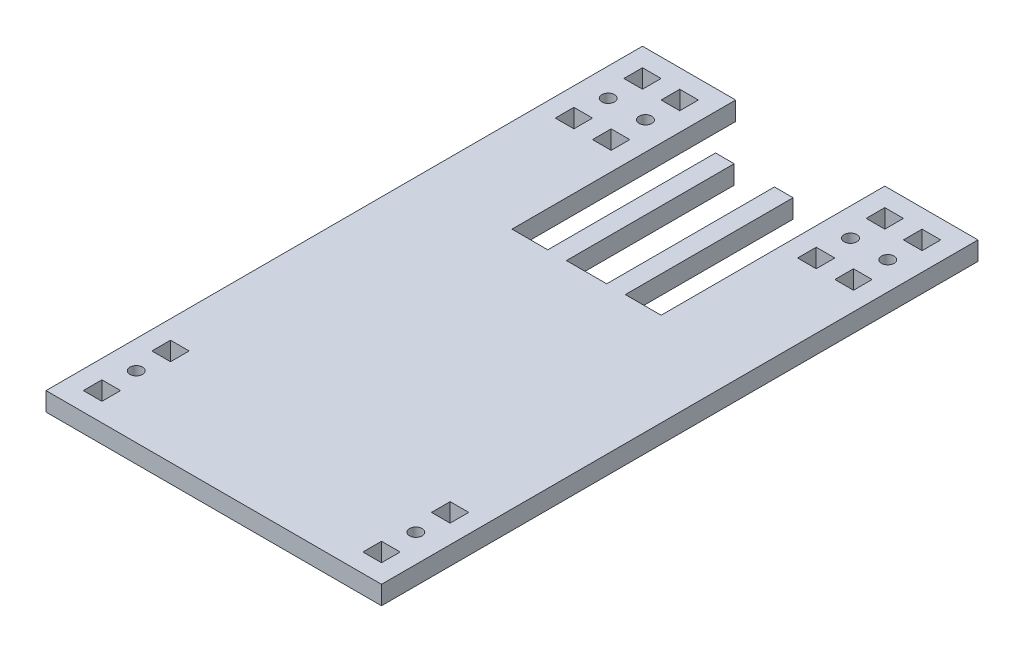
SolidWorks part; units mm, degrees
ref_plane "Front Plane" through (0, 0, 0) normal (0, 0, 1) x (1, 0, 0)
ref_plane "Top Plane" through (0, 0, 0) normal (0, 1, 0) x (1, 0, 0)
ref_plane "Right Plane" through (0, 0, 0) normal (1, 0, 0) x (0, 0, -1)
sketch "Sketch1" plane through (0, 0, 0) normal (0, 1, 0) x (1, 0, 0)
  line L0 (0, 25.4) -> (0, -101.6) construction
  line L1 (-57.15, 101.6) -> (-25.4, 101.6)
  line L2 (-57.15, 101.6) -> (-57.15, -101.6)
  line L3 (-57.15, -101.6) -> (57.15, -101.6)
  line L4 (57.15, 101.6) -> (57.15, -101.6)
  line L5 (-57.15, 101.6) -> (57.15, -101.6) construction
  line L6 (-57.15, -101.6) -> (57.15, 101.6) construction
  line L7 (-57.15, 0) -> (57.15, 0) construction
  line L8 (31.75, 101.6) -> (31.75, -101.6) construction
  line L9 (-31.75, 101.6) -> (-31.75, -101.6) construction
  line L10 (6.858, 82.55) -> (6.858, -101.6) construction
  line L11 (-6.858, 82.55) -> (-6.858, -101.6) construction
  line L12 (-6.858, 82.55) -> (-6.858, 25.4)
  line L13 (-6.858, 25.4) -> (6.858, 25.4)
  line L14 (6.858, 25.4) -> (6.858, 82.55)
  line L15 (6.858, 82.55) -> (13.208, 82.55)
  line L16 (44.45, 101.6) -> (44.45, -101.6) construction
  line L17 (-44.45, 101.6) -> (-44.45, -101.6) construction
  line L18 (13.208, 82.55) -> (13.208, 25.4)
  line L19 (13.208, 25.4) -> (25.4, 25.4)
  line L20 (25.4, 25.4) -> (25.4, 101.6)
  line L21 (25.4, 101.6) -> (57.15, 101.6)
  line L22 (-25.4, 25.4) -> (-25.4, 101.6)
  line L23 (-13.208, 25.4) -> (-25.4, 25.4)
  line L24 (-13.208, 82.55) -> (-13.208, 25.4)
  line L25 (-6.858, 25.4) -> (-6.858, 82.55)
  line L26 (-13.208, 82.55) -> (-6.858, 82.55)
  point P0 (0, 0)
  line B0 (34.925, 65.532) -> (34.925, 95.25) construction
  line B1 (32.766, 80.391) -> (37.084, 80.391) construction
  line B2 (31.75, 88.9) -> (38.1, 88.9)
  line B3 (31.75, 88.9) -> (31.75, 95.25)
  line B4 (31.75, 95.25) -> (38.1, 95.25)
  line B5 (38.1, 88.9) -> (38.1, 95.25)
  line B6 (31.75, 88.9) -> (38.1, 95.25) construction
  line B7 (31.75, 95.25) -> (38.1, 88.9) construction
  line B8 (31.75, 65.532) -> (38.1, 71.882) construction
  line B9 (31.75, 71.882) -> (38.1, 65.532) construction
  line B10 (38.1, 71.882) -> (38.1, 65.532)
  line B11 (31.75, 65.532) -> (38.1, 65.532)
  line B12 (31.75, 71.882) -> (31.75, 65.532)
  line B13 (31.75, 71.882) -> (38.1, 71.882)
  circle B14 centre (34.925, 80.391) radius 2.159
  line B15 (-34.925, 65.532) -> (-34.925, 95.25) construction
  line B16 (-32.766, 80.391) -> (-37.084, 80.391) construction
  line B17 (-31.75, 88.9) -> (-38.1, 88.9)
  line B18 (-31.75, 88.9) -> (-31.75, 95.25)
  line B19 (-31.75, 95.25) -> (-38.1, 95.25)
  line B20 (-38.1, 88.9) -> (-38.1, 95.25)
  line B21 (-31.75, 88.9) -> (-38.1, 95.25) construction
  line B22 (-31.75, 95.25) -> (-38.1, 88.9) construction
  line B23 (-31.75, 65.532) -> (-38.1, 71.882) construction
  line B24 (-31.75, 71.882) -> (-38.1, 65.532) construction
  line B25 (-38.1, 71.882) -> (-38.1, 65.532)
  line B26 (-31.75, 65.532) -> (-38.1, 65.532)
  line B27 (-31.75, 71.882) -> (-31.75, 65.532)
  line B28 (-31.75, 71.882) -> (-38.1, 71.882)
  circle B29 centre (-34.925, 80.391) radius 2.159
  line B30 (47.625, 65.532) -> (47.625, 95.25) construction
  line B31 (45.466, 80.391) -> (49.784, 80.391) construction
  line B32 (44.45, 88.9) -> (50.8, 88.9)
  line B33 (44.45, 88.9) -> (44.45, 95.25)
  line B34 (44.45, 95.25) -> (50.8, 95.25)
  line B35 (50.8, 88.9) -> (50.8, 95.25)
  line B36 (44.45, 88.9) -> (50.8, 95.25) construction
  line B37 (44.45, 95.25) -> (50.8, 88.9) construction
  line B38 (44.45, 65.532) -> (50.8, 71.882) construction
  line B39 (44.45, 71.882) -> (50.8, 65.532) construction
  line B40 (50.8, 71.882) -> (50.8, 65.532)
  line B41 (44.45, 65.532) -> (50.8, 65.532)
  line B42 (44.45, 71.882) -> (44.45, 65.532)
  line B43 (44.45, 71.882) -> (50.8, 71.882)
  circle B44 centre (47.625, 80.391) radius 2.159
  line B45 (-47.625, 65.532) -> (-47.625, 95.25) construction
  line B46 (-45.466, 80.391) -> (-49.784, 80.391) construction
  line B47 (-44.45, 88.9) -> (-50.8, 88.9)
  line B48 (-44.45, 88.9) -> (-44.45, 95.25)
  line B49 (-44.45, 95.25) -> (-50.8, 95.25)
  line B50 (-50.8, 88.9) -> (-50.8, 95.25)
  line B51 (-44.45, 88.9) -> (-50.8, 95.25) construction
  line B52 (-44.45, 95.25) -> (-50.8, 88.9) construction
  line B53 (-44.45, 65.532) -> (-50.8, 71.882) construction
  line B54 (-44.45, 71.882) -> (-50.8, 65.532) construction
  line B55 (-50.8, 71.882) -> (-50.8, 65.532)
  line B56 (-44.45, 65.532) -> (-50.8, 65.532)
  line B57 (-44.45, 71.882) -> (-44.45, 65.532)
  line B58 (-44.45, 71.882) -> (-50.8, 71.882)
  circle B59 centre (-47.625, 80.391) radius 2.159
  line B60 (47.625, -95.25) -> (47.625, -65.532) construction
  line B61 (45.466, -80.391) -> (49.784, -80.391) construction
  line B62 (44.45, -71.882) -> (50.8, -71.882)
  line B63 (44.45, -71.882) -> (44.45, -65.532)
  line B64 (44.45, -65.532) -> (50.8, -65.532)
  line B65 (50.8, -71.882) -> (50.8, -65.532)
  line B66 (44.45, -71.882) -> (50.8, -65.532) construction
  line B67 (44.45, -65.532) -> (50.8, -71.882) construction
  line B68 (44.45, -95.25) -> (50.8, -88.9) construction
  line B69 (44.45, -88.9) -> (50.8, -95.25) construction
  line B70 (50.8, -88.9) -> (50.8, -95.25)
  line B71 (44.45, -95.25) -> (50.8, -95.25)
  line B72 (44.45, -88.9) -> (44.45, -95.25)
  line B73 (44.45, -88.9) -> (50.8, -88.9)
  circle B74 centre (47.625, -80.391) radius 2.159
  line B75 (-47.625, -95.25) -> (-47.625, -65.532) construction
  line B76 (-49.784, -80.391) -> (-45.466, -80.391) construction
  line B77 (-50.8, -71.882) -> (-44.45, -71.882)
  line B78 (-50.8, -71.882) -> (-50.8, -65.532)
  line B79 (-50.8, -65.532) -> (-44.45, -65.532)
  line B80 (-44.45, -71.882) -> (-44.45, -65.532)
  line B81 (-50.8, -71.882) -> (-44.45, -65.532) construction
  line B82 (-50.8, -65.532) -> (-44.45, -71.882) construction
  line B83 (-50.8, -95.25) -> (-44.45, -88.9) construction
  line B84 (-50.8, -88.9) -> (-44.45, -95.25) construction
  line B85 (-44.45, -88.9) -> (-44.45, -95.25)
  line B86 (-50.8, -95.25) -> (-44.45, -95.25)
  line B87 (-50.8, -88.9) -> (-50.8, -95.25)
  line B88 (-50.8, -88.9) -> (-44.45, -88.9)
  circle B89 centre (-47.625, -80.391) radius 2.159
  dimension "D1" = 63.5
  dimension "D2" = 6.35
  dimension "D3" = 6.858
  dimension "D4" = 6.35
  dimension "D5" = 6.35
  dimension "D6" = 203.2
  dimension "D7" = 19.05
  dimension "D8" = 6.35
  dimension "D9" = 6.35
  dimension "D10" = 6.35
  dimension "D11" = 6.35
  dimension "D12" = 76.2
sketch_block_instance "Female T-Slot Assembly-1"
sketch_block "Female T-Slot Assembly" parameters "D4"=4.318, "D1"=6.35, "D2"=6.35, "D3"=6.35
sketch_block_instance "Female T-Slot Assembly-3"
sketch_block_instance "Female T-Slot Assembly-5"
sketch_block_instance "Female T-Slot Assembly-10"
sketch_block_instance "Female T-Slot Assembly-1"
sketch_block_instance "Female T-Slot Assembly-1"
extrude "Boss-Extrude1" add sketch "Sketch1" along normal blind 6.35 contours L26 L24 L23 L22 L1 L2 L3 L4 L21 L20 L19 L18 L15 L14 L13 L12 B89 B72 B73 B70 B71 B65 B62 B63 B64 B47 B50 B49 B48 B44 B29 B28 B27 B26 B25 B12 B13 B10 B11 B5 B2 B3
equation "\"Ball Diameter\"= 1.75in"
equation "\"Ball Radius\" = \"Ball Diameter\"/2"
equation "\"Sheet Thickness\"= 0.25in"
equation "\"Screw Diameter\"= .17in"
equation "\"Robot Diameter\"= 14in"
equation "\"Castor Screw Diameter\"= 0.22in"
equation "\"Wheel Diameter\" = 4in"
equation "\"Nut Diameter\" = 8.4mm"
equation "\"Nut Height\" = 2.9mm"
equation "\"Screw Height\" = 0.55in"
equation "\"Pulley Diameter\" = 1in"
equation "\"Reactor Height\" = 14in"
equation "\"Elevator Height\" = 11.5in"
equation "\"Elevator Width\" = \"Ball Diameter\" + 0.25in"
equation "\"Elevator Bearing Diameter\" = sqr(2*(\"Sheet Thickness\"^2)) + 0.2in"
equation "\"Elevator Axle Endcap Diameter\" = \"Pulley Diameter\" + 0.25in"
equation "\"Elevator Axle Length\" = \"Elevator Width\" + 8*\"Sheet Thickness\""
equation "\"Elevator Clearance from Axis\" = 3.28in"
equation "\"Elevator Horizontal Clearance\" = \"Elevator Width\" + 0.5in"
equation "\"Claw Horizontal Seperation\" = (\"Elevator Width\"/2) - (1.5 * \"Sheet Thickness\") - 0.15in"
equation "\"Claw Radius\" = \"Ball Radius\" + 0.1in"
equation "\"Castor Wheel Height\" = 1.25in"
equation "\"Length of Chute\" = 8in"
equation "\"D6@Sketch1\"=\"Length of Chute\""
